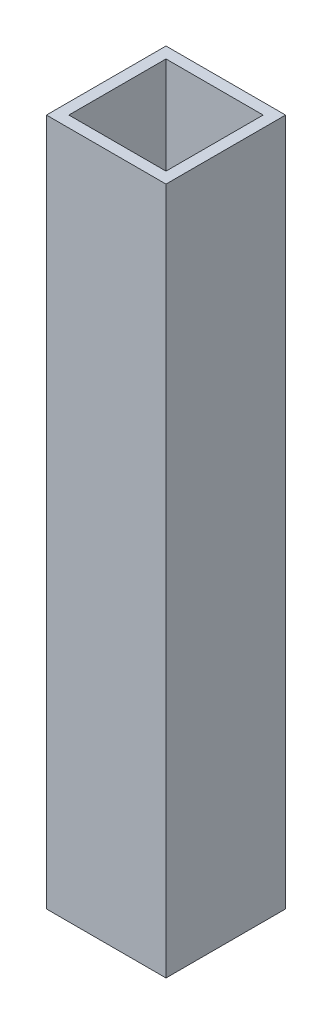
SolidWorks part; units mm, degrees
ref_plane "Front Plane" through (0, 0, 0) normal (0, 0, 1) x (1, 0, 0)
ref_plane "Top Plane" through (0, 0, 0) normal (0, 1, 0) x (1, 0, 0)
ref_plane "Right Plane" through (0, 0, 0) normal (1, 0, 0) x (0, 0, -1)
sketch "Sketch1" plane through (0, 0, 0) normal (0, 0, 1) x (1, 0, 0)
  line L1 (-25.4, 146.05) -> (25.4, 146.05)
  line L2 (-25.4, 146.05) -> (-25.4, -146.05)
  line L3 (-25.4, -146.05) -> (25.4, -146.05)
  line L4 (25.4, 146.05) -> (25.4, -146.05)
  line L5 (-25.4, 146.05) -> (25.4, -146.05) construction
  line L6 (-25.4, -146.05) -> (25.4, 146.05) construction
  point P0 (0, 0)
  dimension "D1" = 50.8
  dimension "D2" = 292.1
extrude "Boss-Extrude1" add sketch "Sketch1" along normal blind 50.8
sketch "Sketch3" plane through (0, 146.05, 0) normal (0, 1, 0) x (1, 0, 0)
  line L8 (-20.6375, -4.7625) -> (-20.6375, -46.0375)
  line L9 (-20.6375, -46.0375) -> (20.6375, -46.0375)
  line L10 (20.6375, -46.0375) -> (20.6375, -4.7625)
  line L11 (20.6375, -4.7625) -> (-20.6375, -4.7625)
  line L12 (-20.6375, -4.7625) -> (-20.6375, -46.0375)
  line L13 (-20.6375, -46.0375) -> (20.6375, -46.0375)
  line L14 (20.6375, -46.0375) -> (20.6375, -4.7625)
  line L15 (20.6375, -4.7625) -> (-20.6375, -4.7625)
  dimension "D1" = 4.7625
extrude "Cut-Extrude1" cut sketch "Sketch3" against normal up to next
